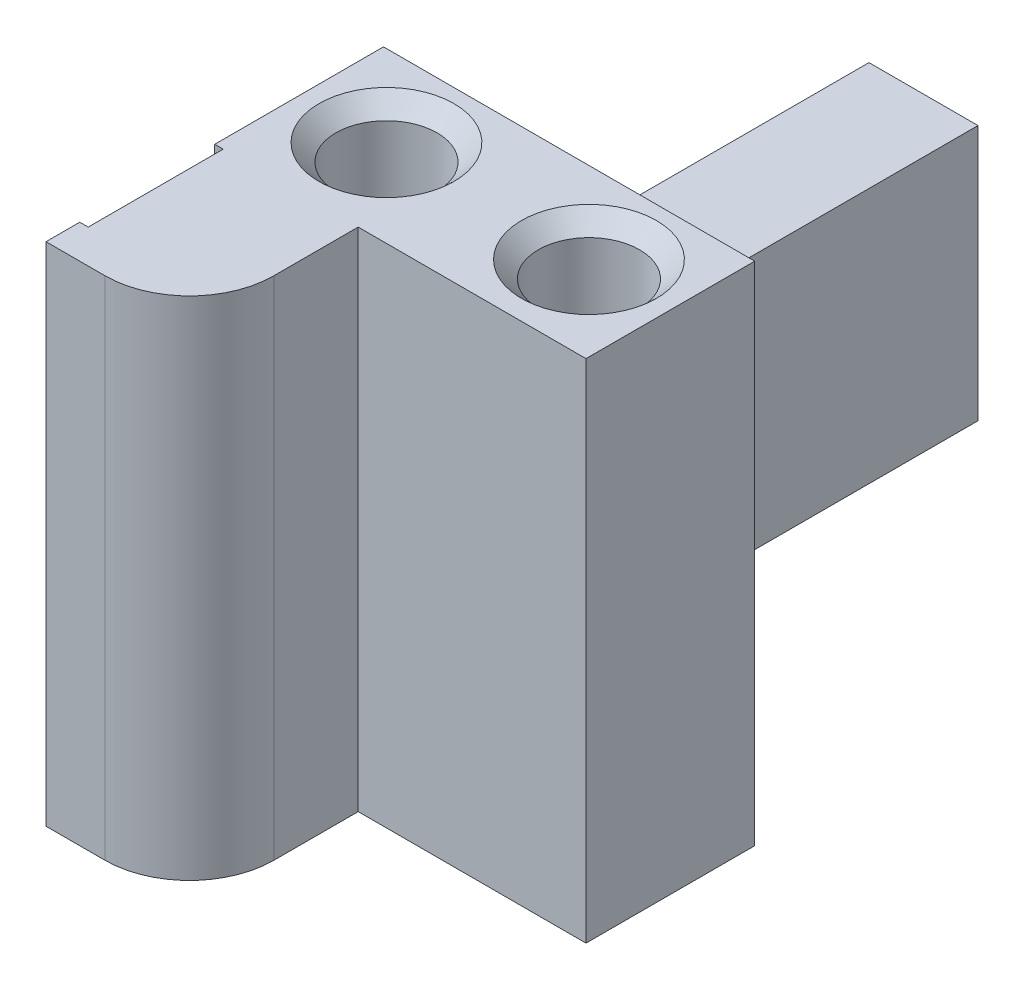
SolidWorks part; units mm, degrees
ref_plane "Front Plane" through (0, 0, 0) normal (0, 0, 1) x (1, 0, 0)
ref_plane "Top Plane" through (0, 0, 0) normal (0, 1, 0) x (1, 0, 0)
ref_plane "Right Plane" through (0, 0, 0) normal (1, 0, 0) x (0, 0, -1)
sketch "Sketch1" plane through (0, 0, 0) normal (0, 0, 1) x (1, 0, 0)
  line L1 (-11, -15) -> (11, -15)
  line L2 (-11, -15) -> (-11, 15)
  line L3 (-11, 15) -> (11, 15)
  line L4 (11, -15) -> (11, 15)
  line L5 (-11, -15) -> (11, 15) construction
  line L6 (-11, 15) -> (11, -15) construction
  point P0 (0, 0)
  dimension "D1" = 30
  dimension "D2" = 22
extrude "Boss-Extrude1" add sketch "Sketch1" along normal blind 10
sketch "Sketch2" plane through (0, 15, 0) normal (0, 1, 0) x (1, 0, 0)
  line L0 (-11, -10) -> (-11, 0) construction
  line L1 (11, -10) -> (11, 0) construction
  circle A0 centre (-6, -4.8244) radius 3
  circle A1 centre (6, -4.8244) radius 3
  point P8 (11, -5)
  dimension "D1" = 5
  dimension "D2" = 5
extrude "Cut-Extrude1" cut sketch "Sketch2" against normal blind 44
sketch "Sketch3" plane through (0, 0, 10) normal (0, 0, 1) x (1, 0, 0)
  line L0 (-11, -15) -> (11, -15) construction
  line L1 (-11, 15) -> (-2.5, 15)
  line L2 (-11, 15) -> (-11, -15)
  line L3 (-11, -15) -> (-2.5, -15)
  line L4 (-2.5, 15) -> (-2.5, -15)
  dimension "D1" = 8.5
extrude "Boss-Extrude2" add sketch "Sketch3" along normal blind 10
ref_plane "Plane1" through (0, 0, 18) normal (0, 0, 1) x (1, 0, 0)
sketch "Sketch4" plane through (0, 0, 18) normal (0, 0, 1) x (1, 0, 0)
  line L4 (-9, 15) -> (-9, -15)
  line L5 (-10.5, 15) -> (-10.5, -15)
  line L6 (-10.5, -14) -> (-9, -14)
  line L7 (-10.5, -13) -> (-9, -13)
  line L8 (-10.5, -12) -> (-9, -12)
  line L9 (-10.5, -11) -> (-9, -11)
  line L10 (-10.5, -8) -> (-9, -8)
  line L11 (-10.5, -9) -> (-9, -9)
  line L12 (-10.5, -10) -> (-9, -10)
  line L13 (-10.5, -6) -> (-9, -6)
  line L14 (-10.5, -7) -> (-9, -7)
  line L15 (-10.5, -5) -> (-9, -5)
  line L16 (-10.5, -4) -> (-9, -4)
  line L17 (-10.5, -3) -> (-9, -3)
  line L18 (-10.5, -2) -> (-9, -2)
  line L19 (-10.5, -1) -> (-9, -1)
  line L20 (-10.5, 0) -> (-9, 0)
  line L21 (-10.5, 1) -> (-9, 1)
  line L22 (-10.5, 3) -> (-9, 3)
  line L23 (-10.5, 2) -> (-9, 2)
  line L24 (-10.5, 6) -> (-9, 6)
  line L25 (-10.5, 5) -> (-9, 5)
  line L26 (-10.5, 4) -> (-9, 4)
  line L27 (-10.5, 7) -> (-9, 7)
  line L28 (-10.5, 8) -> (-9, 8)
  line L29 (-2.5, 15) -> (-11, 15) construction
  line L31 (-11, -15) -> (-2.5, -15) construction
  line L32 (-11, 15) -> (-11, -15) construction
  line L33 (-9, 15) -> (-11, 15)
  line L35 (-11, -15) -> (-9, -15)
  line L36 (-11, 15) -> (-11, -15)
  line L37 (-10.5, 9) -> (-9, 9)
  line L38 (-10.5, 10) -> (-9, 10)
  line L39 (-10.5, 11) -> (-9, 11)
  line L40 (-10.5, 12) -> (-9, 12)
  line L41 (-10.5, 13) -> (-9, 13)
  line L42 (-10.5, 14) -> (-9, 14)
  dimension "D1" = 2
  dimension "D2" = 1.5
  dimension "D3" = 1
  dimension "D4" = 1
  dimension "D5" = 1
  dimension "D6" = 1
extrude "Cut-Extrude2" cut sketch "Sketch4" against normal blind 8 contours L33 L36 L35 L5 | L42 L5 L41 L4 | L40 L5 L39 L4 | L38 L5 L37 L4 | L28 L5 L27 L4 | L5 L25 L4 L24 | L26 L5 L22 L4 | L23 L5 L21 L4 | L20 L5 L19 L4 | L18 L5 L17 L4 | L16 L5 L15 L4 | L5 L14 L4 L13 | L5 L11 L4 L10 | L12 L5 L9 L4 | L8 L5 L7 L4 | L5 L35 L4 L6
sketch "Sketch5" plane through (0, 0, 0) normal (0, 0, -1) x (-1, 0, 0)
  line L1 (-3.2302, 7.5761) -> (3.2302, 7.5761)
  line L2 (-3.2302, 7.5761) -> (-3.2302, -7.5761)
  line L3 (-3.2302, -7.5761) -> (3.2302, -7.5761)
  line L4 (3.2302, 7.5761) -> (3.2302, -7.5761)
  line L5 (-3.2302, 7.5761) -> (3.2302, -7.5761) construction
  line L6 (-3.2302, -7.5761) -> (3.2302, 7.5761) construction
  point P0 (0, 0)
extrude "Boss-Extrude3" add sketch "Sketch5" along normal blind 21
chamfer "Chamfer1" distance 1 angle 45 4 edges at (-6, -15, 7.8244) (-6, 15, 7.8244) (6, -15, 7.8244) (6, 15, 7.8244)
fillet "Fillet1" radius 5 1 edges at (-2.5, 0, 20)
